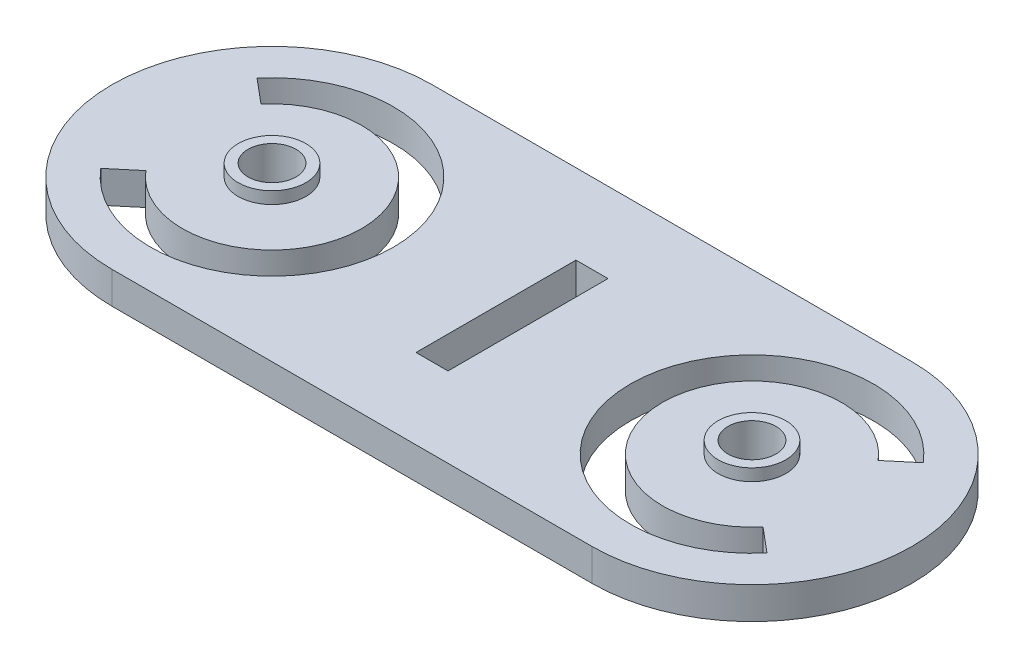
SolidWorks part; units mm, degrees
material "PLA"
ref_plane "Front Plane" through (0, 0, 0) normal (0, 0, 1) x (1, 0, 0)
ref_plane "Top Plane" through (0, 0, 0) normal (0, 1, 0) x (1, 0, 0)
ref_plane "Right Plane" through (0, 0, 0) normal (1, 0, 0) x (0, 0, -1)
sketch "Sketch1" plane through (0, 0, 0) normal (0, 1, 0) x (1, 0, 0)
  line L0 (-30, 0) -> (30, 0) construction
  line L1 (-30, 20) -> (30, 20)
  line L2 (-30, -20) -> (30, -20)
  arc A0 (-30, 20) -> (-30, -20) centre (-30, 0) ccw
  arc A1 (30, -20) -> (30, 20) centre (30, 0) ccw
  point P2 (0, 0)
  point P8 (0, 0)
  dimension "D1" = 60
  dimension "D2" = 40
extrude "Boss-Extrude1" add sketch "Sketch1" along normal blind 4
sketch "Sketch2" plane through (0, 4, 0) normal (0, 1, 0) x (1, 0, 0)
  line L0 (-30, 20) -> (-30, -20) construction
  line L1 (0, -10) -> (0, 10) construction
  line L2 (2, 10) -> (-2, 10)
  line L3 (-30, 0) -> (-38.5759, 0) construction
  line L5 (-2, 10) -> (-2, -10)
  line L6 (-2, -10) -> (2, -10)
  line L7 (2, 10) -> (2, -10)
  line L8 (-30, 0) -> (-41.64, 0) construction
  line L9 (-41.64, 0) -> (-41.64, 9.7672) construction
  line L10 (-38.5759, 0) -> (-38.5759, 7.196) construction
  line L11 (-41.64, 9.7672) -> (-38.5759, 7.196)
  line L12 (-41.64, -9.7672) -> (-38.5759, -7.196)
  line L13 (41.64, -9.7672) -> (38.5759, -7.196)
  line L14 (41.64, 9.7672) -> (38.5759, 7.196)
  arc A2 (-41.64, -9.7672) -> (-41.64, 9.7672) centre (-30, 0) ccw
  arc A3 (-38.5759, -7.196) -> (-38.5759, 7.196) centre (-30, 0) ccw
  circle A4 centre (-30, 0) radius 3
  arc A5 (41.64, -9.7672) -> (41.64, 9.7672) centre (30, 0) cw
  arc A6 (38.5759, -7.196) -> (38.5759, 7.196) centre (30, 0) cw
  circle A7 centre (30, 0) radius 3
  point P3 (-30, 0)
  point P10 (0, 0)
  point P13 (0, 10)
  dimension "D1" = 7.196
  dimension "D2" = 20
  dimension "D3" = 4
  dimension "D5" = 9.7672
extrude "Cut-Extrude1" cut sketch "Sketch2" against normal through all
sketch "Sketch3" plane through (0, 4, 0) normal (0, 1, 0) x (1, 0, 0)
  line L0 (0, -2.2) -> (0, 2.2) construction
  circle A0 centre (-30, 0) radius 4.2333
  circle A3 centre (-30, 0) radius 3
  circle A4 centre (30, 0) radius 3
  circle A5 centre (30, 0) radius 4.2333
  dimension "D1" = 8.4667
extrude "Boss-Extrude2" add sketch "Sketch3" along normal blind 1.5
